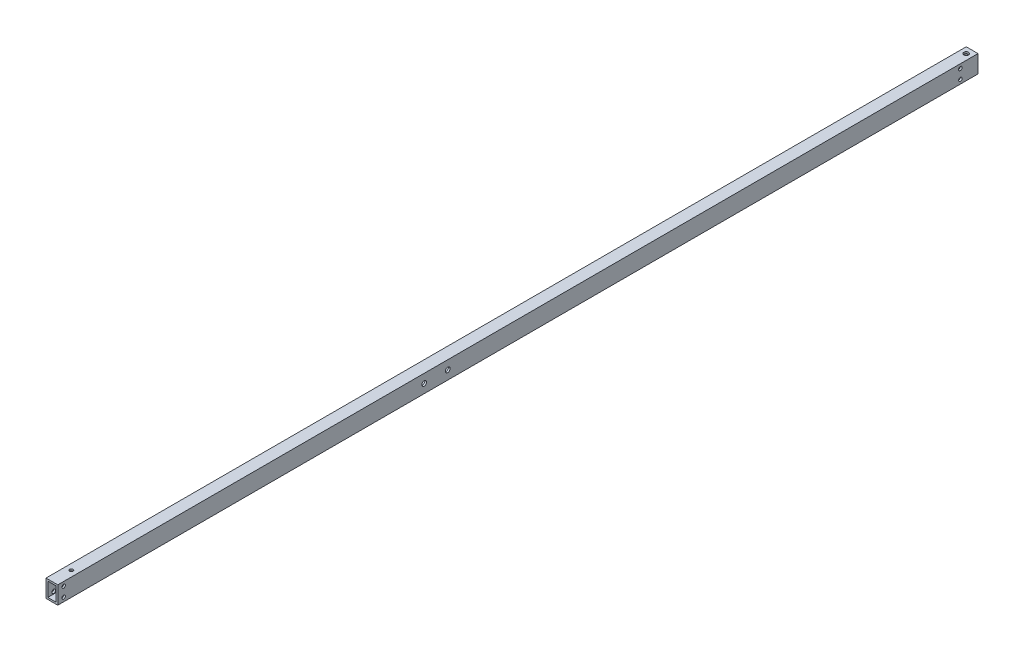
SolidWorks part; units mm, degrees
material "1060 合金"
ref_plane "正面" through (0, 0, 0) normal (0, 0, 1) x (1, 0, 0)
ref_plane "平面" through (0, 0, 0) normal (0, 1, 0) x (1, 0, 0)
ref_plane "右側面" through (0, 0, 0) normal (1, 0, 0) x (0, 0, -1)
sketch "ｽｹｯﾁ1" plane through (0, 0, 0) normal (0, 0, 1) x (1, 0, 0)
  line L1 (-5, -7.5) -> (5, -7.5)
  line L2 (-5, -7.5) -> (-5, 7.5)
  line L3 (-5, 7.5) -> (5, 7.5)
  line L4 (5, -7.5) -> (5, 7.5)
  line L5 (-5, -7.5) -> (5, 7.5) construction
  line L6 (-5, 7.5) -> (5, -7.5) construction
  point P0 (0, 0)
  dimension "D1" = 10
  dimension "D2" = 15
extrude "押し出し-薄板1" add sketch "ｽｹｯﾁ1" along normal blind 781 thin thin type one direction reverse wall 1.5
sketch "ｽｹｯﾁ2" plane through (5, 0, 0) normal (1, 0, 0) x (0, 0, -1)
  line L0 (-328, 0) -> (49672, 0) construction
  line L1 (-781, -7.5) -> (-781, 7.5) construction
  line L2 (-390.5, 10) -> (-390.5, 50010) construction
  line L3 (-781, 7.5) -> (0, 7.5) construction
  line L4 (-460, 7.5) -> (-460, -7.5) construction
  line L5 (0, -7.5) -> (0, 7.5) construction
  line L6 (-781, -7.5) -> (0, -7.5) construction
  circle A5 centre (-470, 0) radius 2
  circle A11 centre (-450, 0) radius 2
  circle A12 centre (-15, 4) radius 1.5
  circle A13 centre (-15, -4) radius 1.5
  circle A14 centre (-776, 4) radius 1.5
  circle A15 centre (-776, -4) radius 1.5
  point P4 (-781, 0)
  point P13 (-390.5, 7.5)
  dimension "D2" = 4
  dimension "D3" = 8
  dimension "D4" = 15
  dimension "D5" = 460
  dimension "D6" = 7.5
  dimension "D7" = 3
  dimension "D8" = 8
  dimension "D9" = 3
  dimension "D10" = 5
  dimension "D11" = 20
extrude "ｶｯﾄ - 押し出し1" cut sketch "ｽｹｯﾁ2" against normal through all
sketch "ｽｹｯﾁ3" plane through (0, 7.5, 0) normal (0, 1, 0) x (1, 0, 0)
  line L0 (0, 0) -> (0, 50000) construction
  line L1 (5, 0) -> (-5, 0) construction
  line L2 (5, -781) -> (-5, -781) construction
  circle A0 centre (0, -5) radius 2
  circle A1 centre (0, -764.5) radius 1.5
  dimension "D1" = 5
  dimension "D2" = 4
  dimension "D3" = 16.5
  dimension "D4" = 3
extrude "ｶｯﾄ - 押し出し2" cut sketch "ｽｹｯﾁ3" against normal through all
